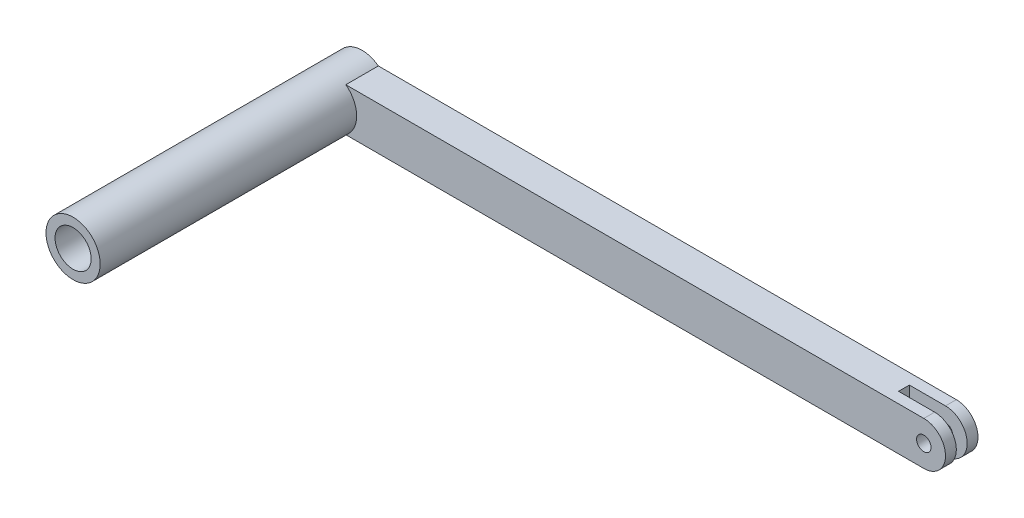
SolidWorks part; units mm, degrees
ref_plane "前视基准面" through (0, 0, 0) normal (0, 0, 1) x (1, 0, 0)
ref_plane "上视基准面" through (0, 0, 0) normal (0, 1, 0) x (1, 0, 0)
ref_plane "右视基准面" through (0, 0, 0) normal (1, 0, 0) x (0, 0, -1)
sketch "草图1" plane through (0, 0, 0) normal (0, 0, 1) x (1, 0, 0)
  circle A0 centre (0, 0) radius 5
  circle A1 centre (0, 0) radius 7.5
  dimension "D1" = 10
  dimension "D2" = 15
extrude "凸台-拉伸1" add sketch "草图1" along normal blind 80
ref_plane "基准面1" through (0, 0, 9) normal (0, 0, 1) x (1, 0, 0)
sketch "草图2" plane through (0, 0, 9) normal (0, 0, 1) x (1, 0, 0)
  line L1 (164.5, -6) -> (4.5, -6)
  line L3 (164.5, 6) -> (4.5, 6)
  line L5 (84.5, 6) -> (84.5, -6) construction
  line L6 (85.1812, 0) -> (4.5, 0) construction
  arc A0 (4.5, -6) -> (4.5, 6) centre (0, 0) ccw
  arc A1 (164.5, 6) -> (164.5, -6) centre (164.5, 0) cw
  circle A2 centre (164.5, 0) radius 2
  point P3 (84.5, 0)
  dimension "D3" = 4
  dimension "D1" = 160
  dimension "D2" = 12
extrude "凸台-拉伸2" add sketch "草图2" against normal blind 9
sketch "草图4" plane through (0, 6, 0) normal (0, 1, 0) x (1, 0, 0)
  line L0 (164.5, 0) -> (164.5, -9) construction
  line L1 (154.5, -3) -> (174.5, -3)
  line L2 (154.5, -3) -> (154.5, -6)
  line L3 (154.5, -6) -> (174.5, -6)
  line L4 (174.5, -3) -> (174.5, -6)
  line L5 (164.5, -6) -> (164.5, -3) construction
  line L6 (154.5, -4.5) -> (174.5, -4.5) construction
  line L7 (4.5, 0) -> (4.5, -9) construction
  point P0 (164.5, -4.5)
  point P8 (4.5, -4.5)
  dimension "D1" = 3
  dimension "D2" = 10
extrude "切除-拉伸1" cut sketch "草图4" against normal blind 20
